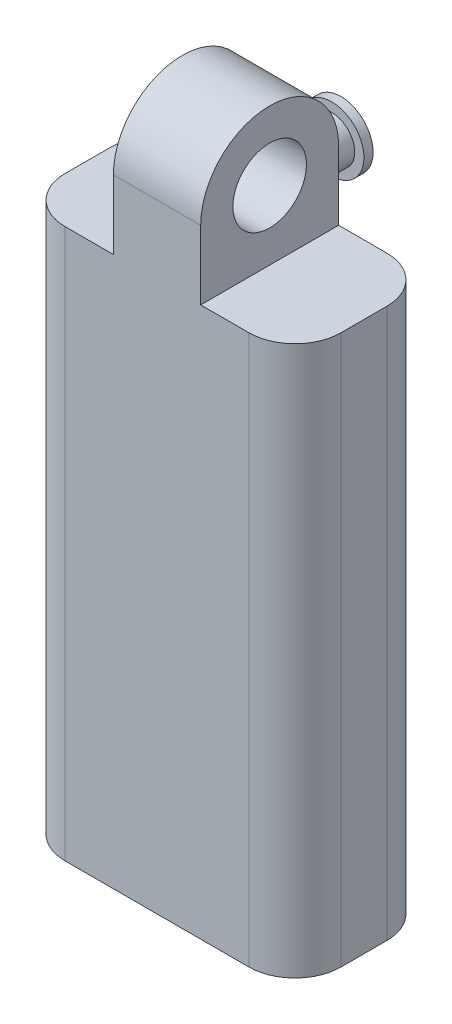
SolidWorks part; units mm, degrees
material "PET"
ref_plane "Front" through (0, 0, 0) normal (0, 0, 1) x (1, 0, 0)
ref_plane "Top" through (0, 0, 0) normal (0, 1, 0) x (1, 0, 0)
ref_plane "Right" through (0, 0, 0) normal (1, 0, 0) x (0, 0, -1)
sketch "Sketch1" plane through (0, 0, 0) normal (0, 1, 0) x (1, 0, 0)
  line L1 (-5, 3.75) -> (5, 3.75)
  line L2 (-7.5, 1.25) -> (-7.5, -1.25)
  line L3 (-5, -3.75) -> (5, -3.75)
  line L4 (7.5, 1.25) -> (7.5, -1.25)
  line L5 (-7.5, 3.75) -> (7.5, -3.75) construction
  line L6 (-7.5, -3.75) -> (7.5, 3.75) construction
  arc A0 (-7.5, -1.25) -> (-5, -3.75) centre (-5, -1.25) ccw
  arc A1 (-5, 3.75) -> (-7.5, 1.25) centre (-5, 1.25) ccw
  arc A2 (5, 3.75) -> (7.5, 1.25) centre (5, 1.25) cw
  arc A3 (5, -3.75) -> (7.5, -1.25) centre (5, -1.25) ccw
  point P0 (0, 0)
  dimension "D3" = 2.5
  dimension "D1" = 15
  dimension "D2" = 7.5
extrude "Boss-Extrude1" add sketch "Sketch1" along normal blind 29.87
sketch "Sketch2" plane through (0, 29.87, 0) normal (0, 1, 0) x (1, 0, 0)
  line L0 (5, 3.75) -> (-5, 3.75) construction
  line L1 (-2.375, -3.75) -> (2.375, -3.75)
  line L2 (-2.375, -3.75) -> (-2.375, 3.75)
  line L3 (-2.375, 3.75) -> (2.375, 3.75)
  line L4 (2.375, -3.75) -> (2.375, 3.75)
  line L5 (-2.375, -3.75) -> (2.375, 3.75) construction
  line L6 (-2.375, 3.75) -> (2.375, -3.75) construction
  point P0 (0, 0)
  point P8 (-2.375, 0)
  dimension "D1" = 4.75
extrude "Boss-Extrude2" add sketch "Sketch2" along normal blind 7.5
sketch "Sketch3" plane through (-2.375, 0, 0) normal (-1, 0, 0) x (0, 0, 1)
  line L0 (-3.75, 33.62) -> (0, 33.62) construction
  line L1 (-3.75, 37.37) -> (-3.75, 29.87) construction
  line L6 (-3.75, 29.87) -> (3.75, 29.87)
  line L7 (3.75, 29.87) -> (3.75, 37.37)
  line L8 (3.75, 37.37) -> (-3.75, 37.37)
  line L9 (-3.75, 37.37) -> (-3.75, 29.87)
  line L11 (3.75, 33.62) -> (3.75, 37.37)
  line L12 (3.75, 37.37) -> (-3.75, 37.37)
  line L13 (-3.75, 37.37) -> (-3.75, 33.62)
  arc A0 (3.75, 33.62) -> (-3.75, 33.62) centre (0, 33.62) ccw
  circle A1 centre (0, 33.62) radius 2
  dimension "D1" = 4
  dimension "D2" = 7.5
  dimension "D3" = 0
extrude "Cut-Extrude1" cut sketch "Sketch3" against normal through all both and the other way through all
sketch "Sketch4" plane through (0, 0, -3.75) normal (0, 0, -1) x (-1, 0, 0)
  line L0 (-2.375, 33.62) -> (2.375, 29.87) construction
  circle A0 centre (0, 31.745) radius 1.25
  dimension "D1" = 2.5
extrude "Boss-Extrude3" add sketch "Sketch4" along normal blind 2
sketch "Sketch5" plane through (0, 0, -5.75) normal (0, 0, -1) x (-1, 0, 0)
  circle A0 centre (0, 31.745) radius 1.75
  dimension "D1" = 3.5
extrude "Boss-Extrude4" add sketch "Sketch5" along normal blind 0.5
